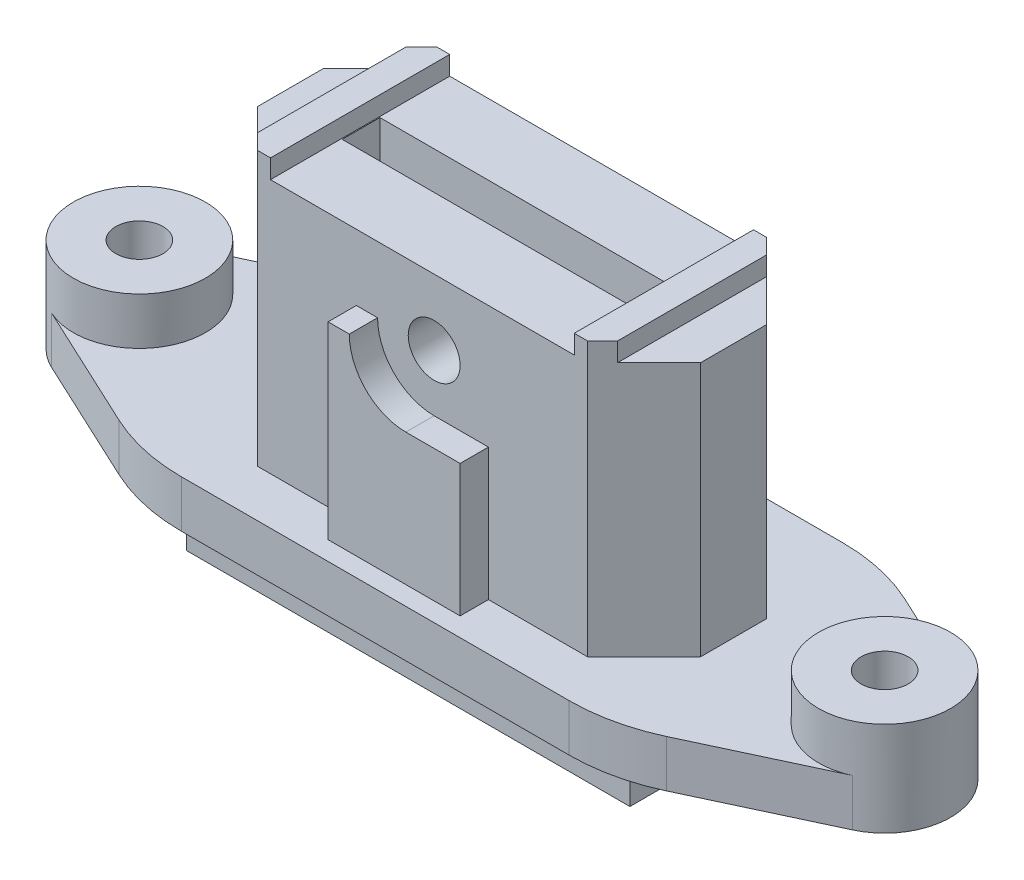
SolidWorks part; units mm, degrees
ref_plane "Front Plane" through (0, 0, 0) normal (0, 0, 1) x (1, 0, 0)
ref_plane "Top Plane" through (0, 0, 0) normal (0, 1, 0) x (1, 0, 0)
ref_plane "Right Plane" through (0, 0, 0) normal (1, 0, 0) x (0, 0, -1)
sketch "Sketch1" plane through (0, 0, 0) normal (0, 1, 0) x (1, 0, 0)
  line L1 (11.75, 5.5) -> (-11.75, 5.5)
  line L2 (11.75, 5.5) -> (11.75, -5.5)
  line L3 (11.75, -5.5) -> (-11.75, -5.5)
  line L4 (-11.75, 5.5) -> (-11.75, -5.5)
  point P0 (0, 0)
  point P6 (-11.75, 0)
  point P7 (0, 5.5)
  dimension "D1" = 23.5
  dimension "D2" = 11
extrude "Boss-Extrude1" add sketch "Sketch1" along normal blind 2.5
ref_plane "Plane1" through (0, 2.5, 0) normal (0, 1, 0) x (1, 0, 0)
sketch "Sketch2" plane through (0, 2.5, 0) normal (0, 1, 0) x (1, 0, 0)
  line L0 (21.2314, -3.171) -> (14.5119, -6.3101)
  line L1 (10.2794, -7.25) -> (-10.2794, -7.25)
  line L3 (10.2794, 7.25) -> (-10.2794, 7.25)
  line L5 (-21.2314, 3.171) -> (-14.5119, 6.3101)
  line L6 (-21.2314, -3.171) -> (-14.5119, -6.3101)
  line L7 (21.2314, 3.171) -> (14.5119, 6.3101)
  arc A0 (21.2314, -3.171) -> (21.2314, 3.171) centre (19.75, 0) ccw
  arc A1 (-21.2314, 3.171) -> (-21.2314, -3.171) centre (-19.75, 0) ccw
  arc A2 (-14.5119, -6.3101) -> (-10.2794, -7.25) centre (-10.2794, 2.75) ccw
  arc A3 (-14.5119, 6.3101) -> (-10.2794, 7.25) centre (-10.2794, -2.75) cw
  arc A4 (10.2794, 7.25) -> (14.5119, 6.3101) centre (10.2794, -2.75) cw
  arc A5 (10.2794, -7.25) -> (14.5119, -6.3101) centre (10.2794, 2.75) ccw
  point P0 (0, 0)
  point P1 (0, 7.25)
  point P7 (0, -7.25)
  point P20 (-12.5, -7.25)
  point P23 (-12.5, 7.25)
  point P26 (12.5, 7.25)
  point P29 (12.5, -7.25)
  dimension "D3" = 7
  dimension "D4" = 7
  dimension "D10" = 10
  dimension "D1" = 39.5
  dimension "D2" = 25
  dimension "D5" = 25
  dimension "D6" = 14.5
  dimension "D7" = 7.25
  dimension "D8" = 25.04
  dimension "D9" = 25.04
extrude "Boss-Extrude2" add sketch "Sketch2" along normal blind 2.5
ref_plane "Plane2" through (0, 5, 0) normal (0, 1, 0) x (1, 0, 0)
sketch "Sketch3" plane through (0, 5, 0) normal (0, 1, 0) x (1, 0, 0)
  line L0 (8.75, -4.75) -> (3.5, -4.75)
  line L1 (3.5, -4.75) -> (3.5, -6.25)
  line L2 (3.5, -6.25) -> (-3.5, -6.25)
  line L3 (-3.5, -6.25) -> (-3.5, -4.75)
  line L4 (-3.5, -4.75) -> (-8.75, -4.75)
  line L5 (-8.75, -4.75) -> (-11.75, -1.75)
  line L6 (-11.75, -1.75) -> (-11.75, 1.75)
  line L7 (-11.75, 1.75) -> (-8.75, 4.75)
  line L8 (-8.75, 4.75) -> (8.75, 4.75)
  line L9 (8.75, 4.75) -> (11.75, 1.75)
  line L10 (11.75, 1.75) -> (11.75, -1.75)
  line L11 (11.75, -1.75) -> (8.75, -4.75)
  point P19 (0, 4.75)
  point P21 (11.75, 0)
  point P22 (0, -6.25)
  dimension "D1" = 23.5
  dimension "D2" = 17.5
  dimension "D3" = 17.5
  dimension "D4" = 3.5
  dimension "D5" = 3.5
  dimension "D6" = 3
  dimension "D7" = 1.5
  dimension "D8" = 7
extrude "Boss-Extrude3" add sketch "Sketch3" along normal blind 13.5
ref_plane "Plane4" through (0, 18.5, 0) normal (0, 1, 0) x (1, 0, 0)
sketch "Sketch5" plane through (0, 18.5, 0) normal (0, 1, 0) x (1, 0, 0)
  line L1 (8.75, 4.75) -> (8.05, 4.75)
  line L2 (9.55, 3.95) -> (9.55, -3.95)
  line L3 (8.75, -4.75) -> (8.05, -4.75)
  line L4 (8.05, 4.75) -> (8.05, -4.75)
  line L5 (3.5, -4.75) -> (8.75, -4.75) construction
  line L6 (11.75, -1.75) -> (11.75, 1.75) construction
  line L7 (8.75, -4.75) -> (9.55, -3.95)
  line L8 (8.75, -4.75) -> (11.75, -1.75) construction
  line L9 (8.75, 4.75) -> (9.55, 3.95)
  line L10 (11.75, 1.75) -> (8.75, 4.75) construction
  line L11 (8.75, 4.75) -> (-8.75, 4.75) construction
  line L12 (-8.05, 4.75) -> (-8.75, 4.75)
  line L13 (-8.05, 4.75) -> (-8.05, -4.75)
  line L14 (-8.05, -4.75) -> (-8.75, -4.75)
  line L15 (-9.55, 3.95) -> (-9.55, -3.95)
  line L17 (-11.75, 1.75) -> (-11.75, -1.75) construction
  line L18 (-8.75, -4.75) -> (-9.55, -3.95)
  line L19 (-11.75, -1.75) -> (-8.75, -4.75) construction
  line L20 (-8.75, 4.75) -> (-9.55, 3.95)
  line L21 (-8.75, 4.75) -> (-11.75, 1.75) construction
  dimension "D1" = 1.5
  dimension "D2" = 3.7
  dimension "D3" = 3.7
  dimension "D4" = 1.5
extrude "Boss-Extrude4" add sketch "Sketch5" along normal blind 1
sketch "Sketch6" plane through (0, 0, 0) normal (0, 1, 0) x (1, 0, 0)
  line L0 (8.4, 3.45) -> (5.1, 3.45)
  line L1 (-8.4, 3.45) -> (-10.35, 1.5)
  line L2 (-10.35, 1.5) -> (-10.35, -1.5)
  line L3 (-10.35, -1.5) -> (-8.4, -3.45)
  line L4 (-8.4, -3.45) -> (-2.05, -3.45)
  line L5 (-2.05, -3.45) -> (-2.05, -4.55)
  line L6 (-2.05, -4.55) -> (2.05, -4.55)
  line L7 (2.05, -4.55) -> (2.05, -3.45)
  line L8 (2.05, -3.45) -> (8.4, -3.45)
  line L9 (8.4, -3.45) -> (10.35, -1.5)
  line L10 (10.35, -1.5) -> (10.35, 1.5)
  line L11 (10.35, 1.5) -> (8.4, 3.45)
  line L13 (-5.1, 3.45) -> (-4.6, 2.95)
  line L14 (-4.6, 2.95) -> (-4.1, 2.95)
  line L15 (-4.1, 2.95) -> (-3.6, 3.45)
  line L16 (3.6, 3.45) -> (4.1, 2.95)
  line L17 (4.1, 2.95) -> (4.6, 2.95)
  line L18 (4.6, 2.95) -> (5.1, 3.45)
  line L19 (-5.1, 3.45) -> (-8.4, 3.45)
  line L20 (3.6, 3.45) -> (-3.6, 3.45)
  point P2 (5.225, -3.45)
  point P13 (-4.35, 2.95)
  point P19 (4.35, 2.95)
  point P24 (10.35, 0)
  point P25 (0, -4.55)
  dimension "D1" = 6.9
  dimension "D2" = 3
  dimension "D3" = 20.7
  dimension "D4" = 45
  dimension "D5" = 8
  dimension "D6" = 4.1
  dimension "D7" = 45
  dimension "D8" = 0.5
  dimension "D9" = 0.5
  dimension "D10" = 6
  dimension "D11" = 45
  dimension "D12" = 6
  dimension "D13" = 0.5
  dimension "D14" = 20.9163
  dimension "D15" = 18.1618
  dimension "D16" = 10.35
extrude "Cut-Extrude1" cut sketch "Sketch6" along normal blind 12
sketch "Sketch7" plane through (0, 0, 0) normal (0, 1, 0) x (1, 0, 0)
  line L1 (-8, -1) -> (8, -1)
  line L2 (-8, -1) -> (-8, 1)
  line L3 (-8, 1) -> (8, 1)
  line L4 (8, -1) -> (8, 1)
  point P4 (-8, 0)
  point P6 (0, 1)
  dimension "D1" = 16
  dimension "D2" = 2
extrude "Cut-Extrude2" cut sketch "Sketch7" along normal through all
ref_plane "Plane5" through (0, 0, 6.25) normal (0, 0, 1) x (1, 0, 0)
sketch "Sketch8" plane through (0, 0, 6.25) normal (0, 0, 1) x (1, 0, 0)
  line L1 (6.05, 18.5) -> (-6.05, 18.5) construction
  line L2 (11.75, 18.5) -> (11.75, 5) construction
  circle A0 centre (0.625, 15) radius 1.375
  dimension "D1" = 2.75
  dimension "D2" = 3.5
  dimension "D3" = 11.125
extrude "Cut-Extrude3" cut sketch "Sketch8" against normal blind 12 contours A0
sketch "Sketch9" plane through (0, 0, 6.25) normal (0, 0, 1) x (1, 0, 0)
  line L0 (0.625, 12) -> (3.5, 12)
  line L1 (3.5, 18.5) -> (3.5, 5) construction
  line L2 (3.5, 12) -> (3.5, 18.5)
  line L3 (-2.375, 15) -> (-3.5, 15)
  line L4 (-3.5, 18.5) -> (-3.5, 5) construction
  line L5 (-3.5, 15) -> (-3.5, 18.5)
  line L6 (6.05, 18.5) -> (-6.05, 18.5) construction
  line L7 (3.5, 18.5) -> (-3.5, 18.5)
  arc A0 (-2.375, 15) -> (0.625, 12) centre (0.625, 15) ccw
  dimension "D1" = 6
extrude "Cut-Extrude5" cut sketch "Sketch9" against normal up to surface (1.5 mm away) up to face at (-6.7667, 14.3333, 4.75)
sketch "Sketch10" plane through (0, 5, 0) normal (0, 1, 0) x (1, 0, 0)
  circle A0 centre (-19.75, 0) radius 3.5
  circle A2 centre (19.75, 0) radius 3.5
extrude "Boss-Extrude5" add sketch "Sketch10" along normal blind 2.5
sketch "Sketch11" plane through (0, 5, 0) normal (0, 1, 0) x (1, 0, 0)
  circle A0 centre (19.75, 0) radius 1.25
  circle A1 centre (-19.75, 0) radius 1.25
  dimension "D1" = 2.5
extrude "Cut-Extrude6" cut sketch "Sketch11" against normal through all both and the other way through all
